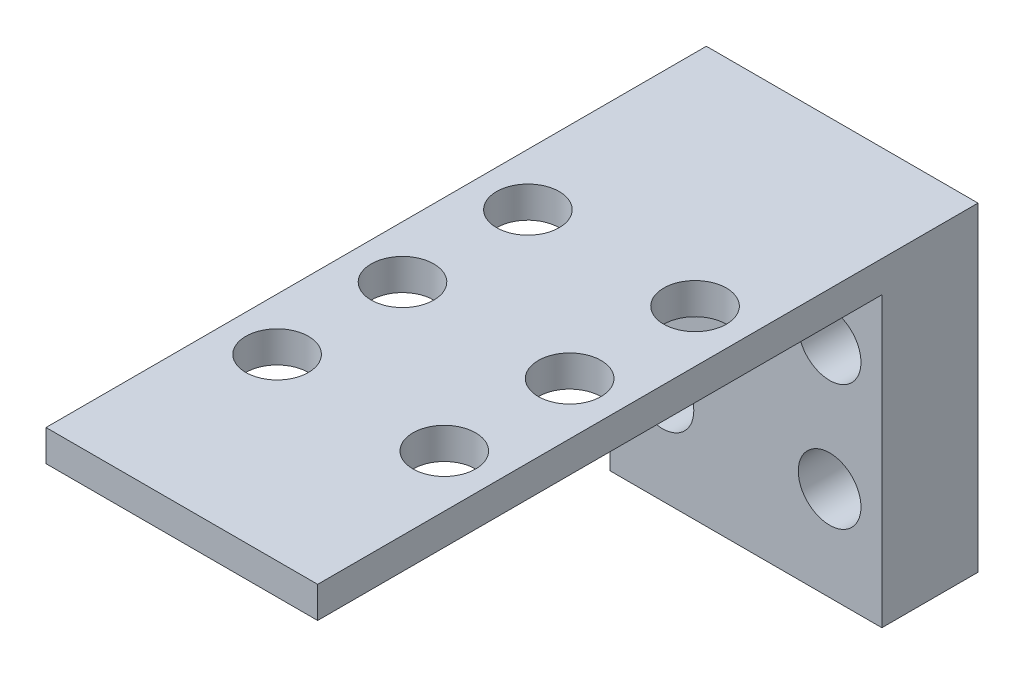
SolidWorks part; units mm, degrees
ref_plane "Front Plane" through (0, 0, 0) normal (0, 0, 1) x (1, 0, 0)
ref_plane "Top Plane" through (0, 0, 0) normal (0, 1, 0) x (1, 0, 0)
ref_plane "Right Plane" through (0, 0, 0) normal (1, 0, 0) x (0, 0, -1)
sketch "Sketch2" plane through (0, 0, 0) normal (0, 0, 1) x (1, 0, 0)
  line L0 (1, 2.9168) -> (1, -0.0094) construction
  line L2 (-5.5, 7.6037) -> (7.5, 7.6037)
  line L3 (-5.5, 7.6037) -> (-5.5, -4.6963)
  line L4 (-5.5, -4.6963) -> (7.5, -4.6963)
  line L5 (7.5, 7.6037) -> (7.5, -4.6963)
  line L6 (-5.5, 7.6037) -> (7.5, -4.6963) construction
  line L7 (-5.5, -4.6963) -> (7.5, 7.6037) construction
  circle A0 centre (-3, 5.8037) radius 1.5
  circle A1 centre (-3, -0.1963) radius 1.5
  circle A2 centre (5, -0.1963) radius 1.5
  circle A3 centre (5, 5.8037) radius 1.5
  point P10 (1, 1.4537)
  point P15 (0, 0)
  dimension "D3" = 3
  dimension "D1" = 6
  dimension "D2" = 4
  dimension "D4" = 4.5
  dimension "D5" = 1.8
  dimension "D6" = 13
extrude "Boss-Extrude1" add sketch "Sketch2" along normal blind 4.6
sketch "Sketch3" plane through (0, 0, 0) normal (0, 1, 0) x (1, 0, 0)
  line L0 (-5.5, -4.6) -> (7.5, -4.6)
  line L1 (7.5, -4.6) -> (7.5, -31.6)
  line L2 (7.5, -31.6) -> (-5.5, -31.6)
  line L3 (-5.5, -31.6) -> (-5.5, -4.6)
  line L4 (1, -4.6) -> (1, -31.6) construction
  line L5 (7.5, -4.6) -> (-5.5, -4.6) construction
  circle A0 centre (-3, -17.04) radius 1.5
  circle A1 centre (-3, -23.04) radius 1.5
  circle A2 centre (5, -23.04) radius 1.5
  circle A3 centre (5, -17.04) radius 1.5
  circle A4 centre (-3, -11.04) radius 1.5
  circle A5 centre (5, -11.04) radius 1.5
  point P20 (0, -15.6935)
  point P21 (0, -4.9177)
  point P22 (0, -2.5)
  point P25 (0, 0)
  point P26 (0, -27.5)
  dimension "D1" = 3
  dimension "D2" = 27
  dimension "D3" = 6.44
  dimension "D4" = 4
  dimension "D5" = 6
  dimension "D6" = 6
extrude "Boss-Extrude2" add sketch "Sketch3" along normal offset from surface (10.6037 mm away) 3 up to face at (1, 7.6037, 2.3) offset beyond the face yes
sketch "Sketch4" plane through (0, 0, 31.6) normal (0, 0, 1) x (1, 0, 0)
  line L0 (7.5, 7.6037) -> (-5.5, 7.6037)
  line L1 (-5.5, 7.6037) -> (-5.5, -4.6963)
  line L2 (-5.5, -4.6963) -> (7.5, -4.6963)
  line L3 (7.5, -4.6963) -> (7.5, 7.6037)
extrude "Cut-Extrude1" cut sketch "Sketch4" against normal up to surface (27 mm away) up to face at (1, -1.5982, 4.6)
sketch "Sketch5" plane through (0, 0, 4.6) normal (0, 0, -1) x (-1, 0, 0)
  line L0 (-7.5, 10.6037) -> (-7.5, 7.6037)
  line L1 (-7.5, 7.6037) -> (5.5, 7.6037)
  line L2 (5.5, 7.6037) -> (5.5, 10.6037)
  line L3 (5.5, 10.6037) -> (-7.5, 10.6037)
extrude "Boss-Extrude3" add sketch "Sketch5" along normal up to surface (4.6 mm away) up to face at (1, 1.4537, 0)
sketch "Sketch7" plane through (0, 7.6037, 0) normal (0, -1, 0) x (1, 0, 0)
  line L0 (-5.5, 31.6) -> (-5.5, 4.6)
  line L1 (-5.5, 4.6) -> (7.5, 4.6)
  line L2 (7.5, 4.6) -> (7.5, 31.6)
  line L3 (7.5, 31.6) -> (-5.5, 31.6)
extrude "Cut-Extrude2" cut sketch "Sketch7" against normal blind 1.5
